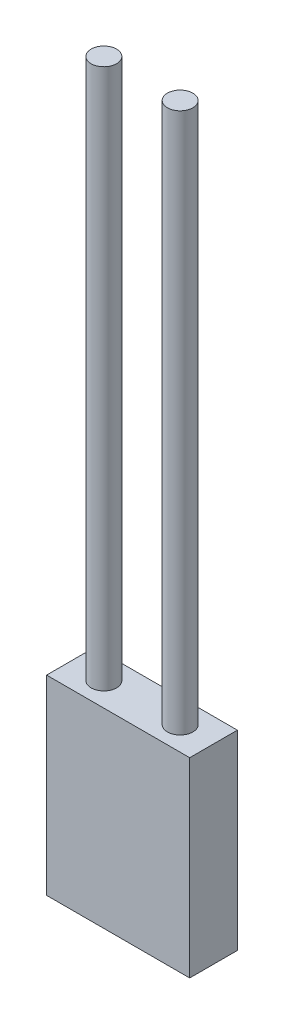
SolidWorks part; units mm, degrees
ref_plane "Alzado" through (0, 0, 0) normal (0, 0, 1) x (1, 0, 0)
ref_plane "Planta" through (0, 0, 0) normal (0, 1, 0) x (1, 0, 0)
ref_plane "Vista lateral" through (0, 0, 0) normal (1, 0, 0) x (0, 0, -1)
sketch "Croquis1" plane through (0, 0, 0) normal (0, 0, 1) x (1, 0, 0)
  line L1 (-22.5, -30) -> (22.5, -30)
  line L2 (-22.5, -30) -> (-22.5, 30)
  line L3 (-22.5, 30) -> (22.5, 30)
  line L4 (22.5, -30) -> (22.5, 30)
  line L5 (-22.5, -30) -> (22.5, 30) construction
  line L6 (-22.5, 30) -> (22.5, -30) construction
  point P0 (0, 0)
  dimension "D1" = 60
  dimension "D2" = 45
extrude "Saliente-Extruir1" add sketch "Croquis1" along normal mid plane 15
sketch "Croquis2" plane through (0, 0, 0) normal (0, 0, 1) x (1, 0, 0)
  line L0 (22.5, 30) -> (-22.5, 30) construction
  line L1 (-16, 30) -> (-12, 30)
  line L2 (-16, 30) -> (-16, 200)
  line L3 (-16, 200) -> (-12, 200)
  line L4 (-12, 30) -> (-12, 200)
  line L5 (0, -3.4408) -> (0, 78.2042) construction
  line L6 (-12, 30) -> (-12, 271.5754) construction
  point P9 (-12, 145.6463)
  point P11 (-12, 271.5754)
  dimension "D1" = 4
  dimension "D2" = 170
  dimension "D3" = 12
revolve "Revolución1" add sketch "Croquis2" angle 360 about L6
mirror "Simetría1" about plane through (0, 0, 0) normal (1, 0, 0) of "Revolución1"
